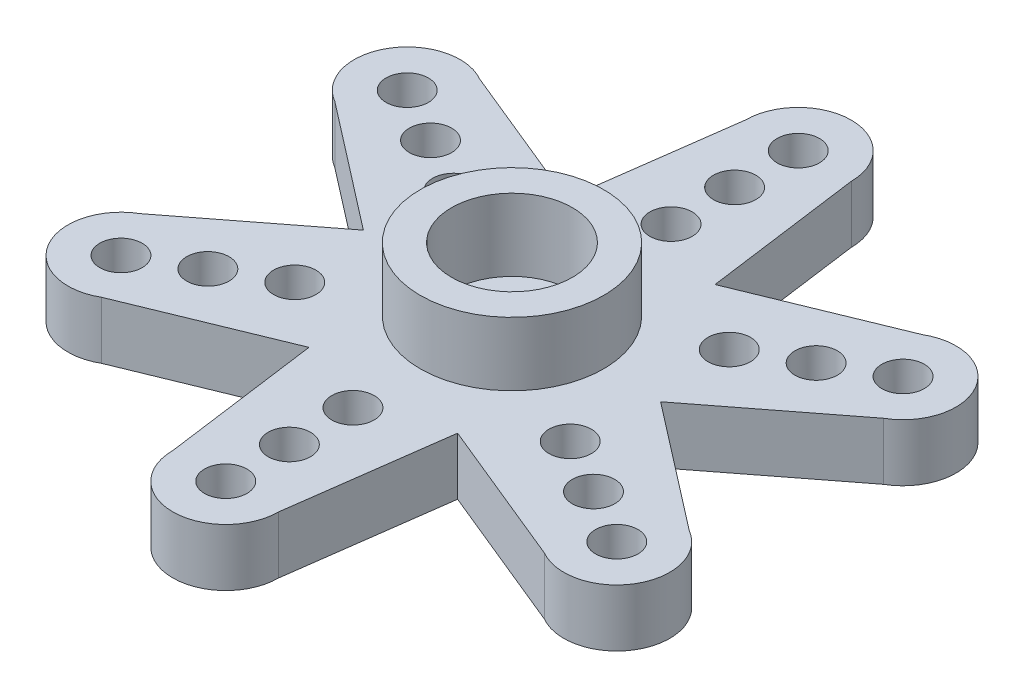
SolidWorks part; units mm, degrees
ref_plane "Plano frontal" through (0, 0, 0) normal (0, 0, 1) x (1, 0, 0)
ref_plane "Plano superior" through (0, 0, 0) normal (0, 1, 0) x (1, 0, 0)
ref_plane "Plano direito" through (0, 0, 0) normal (1, 0, 0) x (0, 0, -1)
sketch "Sketch1" plane through (0, 0, 0) normal (0, 1, 0) x (1, 0, 0)
  circle A0 centre (0, 0) radius 4.325
  dimension "D1" = 8.65
extrude "Boss-Extrude1" add sketch "Sketch1" along normal blind 3
sketch "Sketch2" plane through (0, 0, 0) normal (0, 1, 0) x (1, 0, 0)
  line L1 (-4.325, 0) -> (4.325, 0)
  line L2 (-4.325, 0) -> (-2.5, 13.5)
  line L3 (-2.5, 13.5) -> (2.5, 13.5)
  line L4 (4.325, 0) -> (2.5, 13.5)
  circle A0 centre (0, 13.5) radius 2.5
  circle A1 centre (0, 0) radius 4.325 construction
  point P4 (0, 13.5)
  point P6 (0, 0)
  point P9 (0, 0)
  point P10 (0, 0)
  point P11 (0, 0)
  dimension "D2" = 5
  dimension "D1" = 13.5
extrude "Boss-Extrude2" add sketch "Sketch2" against normal blind 2.7 contours L3 A0
sketch "Sketch3" plane through (0, 0, 0) normal (0, 1, 0) x (1, 0, 0)
  circle A0 centre (0, 13.5) radius 1
  arc A1 (2.5, 13.5) -> (-2.5, 13.5) centre (0, 13.5) ccw construction
  dimension "D1" = 2
extrude "Cut-Extrude1" cut sketch "Sketch3" along direction (0, 1, 0) on the side against the normal up to next (2.7 mm away)
sketch "Sketch4" plane through (0, 0, 0) normal (0, 1, 0) x (1, 0, 0)
  line L0 (0, 0) -> (0, 8.7213) construction
pattern_linear "LPattern1" count 3 spacing 3 along (0, 0, 1) of "Cut-Extrude1"
sketch "Sketch5" plane through (0, 0, 0) normal (0, 0, 1) x (1, 0, 0)
  line L0 (0, 0) -> (0, 4.8161) construction
pattern_circular "CirPattern1" count 6 every 60 about axis through (0, 0, 0) along (0, 1, 0) of "Boss-Extrude2", "Cut-Extrude1", "LPattern1"
sketch "Sketch6" plane through (0, 3, 0) normal (0, 1, 0) x (1, 0, 0)
  circle A0 centre (0, 0) radius 2.85
  dimension "D1" = 5.7
extrude "Cut-Extrude2" cut sketch "Sketch6" against normal blind 3.4
sketch "Sketch7" plane through (0, -0.4, 0) normal (0, 1, 0) x (1, 0, 0)
  circle A0 centre (0, 0) radius 1.5
  dimension "D1" = 3
extrude "Cut-Extrude3" cut sketch "Sketch7" against normal up to next
